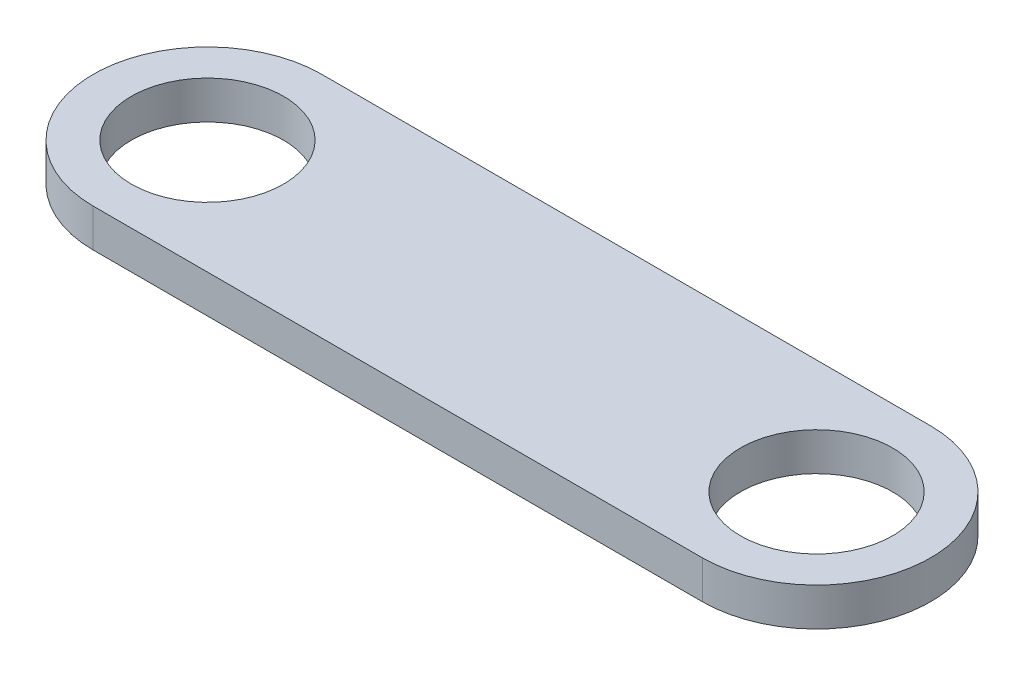
SolidWorks part; units mm, degrees
ref_plane "Front Plane" through (0, 0, 0) normal (0, 0, 1) x (1, 0, 0)
ref_plane "Top Plane" through (0, 0, 0) normal (0, 1, 0) x (1, 0, 0)
ref_plane "Right Plane" through (0, 0, 0) normal (1, 0, 0) x (0, 0, -1)
sketch "Sketch2" plane through (0, 0, 0) normal (0, 1, 0) x (1, 0, 0)
  line L0 (0, 0) -> (50.8, 0) construction
  line L1 (0, 9.525) -> (50.8, 9.525)
  line L2 (0, -9.525) -> (50.8, -9.525)
  arc A0 (0, 9.525) -> (0, -9.525) centre (0, 0) ccw
  arc A1 (50.8, -9.525) -> (50.8, 9.525) centre (50.8, 0) ccw
  circle A2 centre (0, 0) radius 6.35
  circle A3 centre (50.8, 0) radius 6.35
  point P3 (25.4, 0)
  dimension "D3" = 12.7
  dimension "D4" = 12.7
  dimension "D1" = 50.8
  dimension "D2" = 19.05
extrude "Boss-Extrude1" add sketch "Sketch2" along normal blind 3.175
